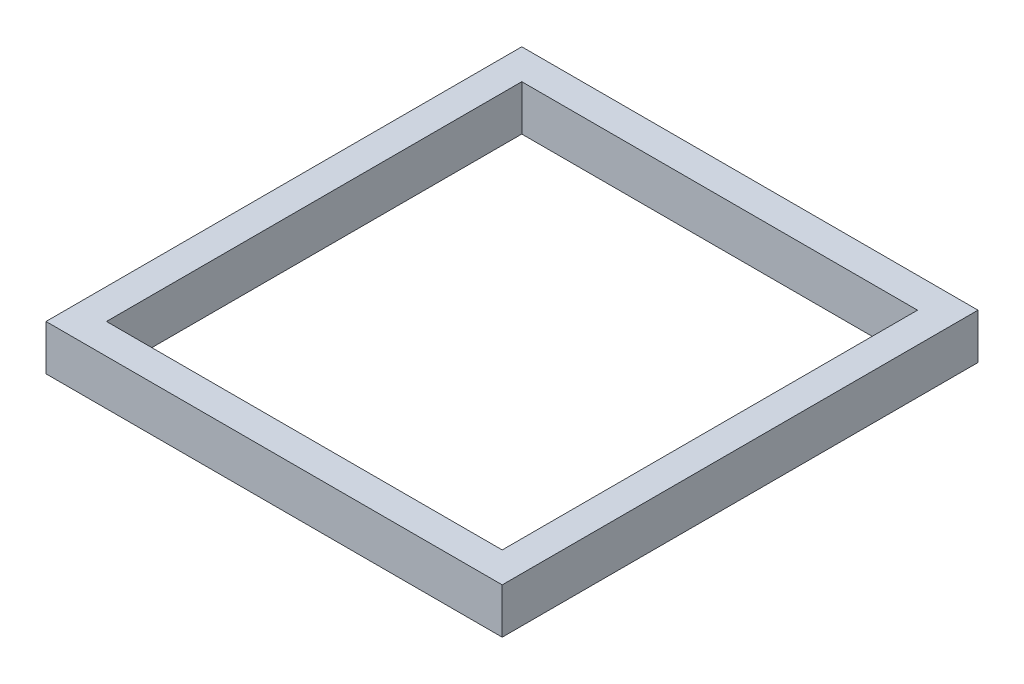
SolidWorks part; units mm, degrees
material "Copper"
ref_plane "Front Plane" through (0, 0, 0) normal (0, 0, 1) x (1, 0, 0)
ref_plane "Top Plane" through (0, 0, 0) normal (0, 1, 0) x (1, 0, 0)
ref_plane "Right Plane" through (0, 0, 0) normal (1, 0, 0) x (0, 0, -1)
sketch "Sketch1" plane through (0, 0, 0) normal (0, 1, 0) x (1, 0, 0)
  line L1 (0, 0) -> (-52.35, 0)
  line L2 (0, 0) -> (0, -54.94)
  line L3 (0, -54.94) -> (-52.35, -54.94)
  line L4 (-52.35, 0) -> (-52.35, -54.94)
  line L8 (4, -54.94) -> (4, 4)
  line L9 (4, 4) -> (-52.35, 4)
  line L10 (-56.35, 4) -> (-56.35, 0)
  line L11 (-56.35, 0) -> (-56.35, -58.94)
  line L12 (-56.35, -58.94) -> (0, -58.94)
  line L13 (0, -58.94) -> (4, -58.94)
  line L14 (4, -58.94) -> (4, -54.94)
  line L15 (-52.35, 4) -> (-56.35, 4)
extrude "Boss-Extrude1" add sketch "Sketch1" along normal blind 6
